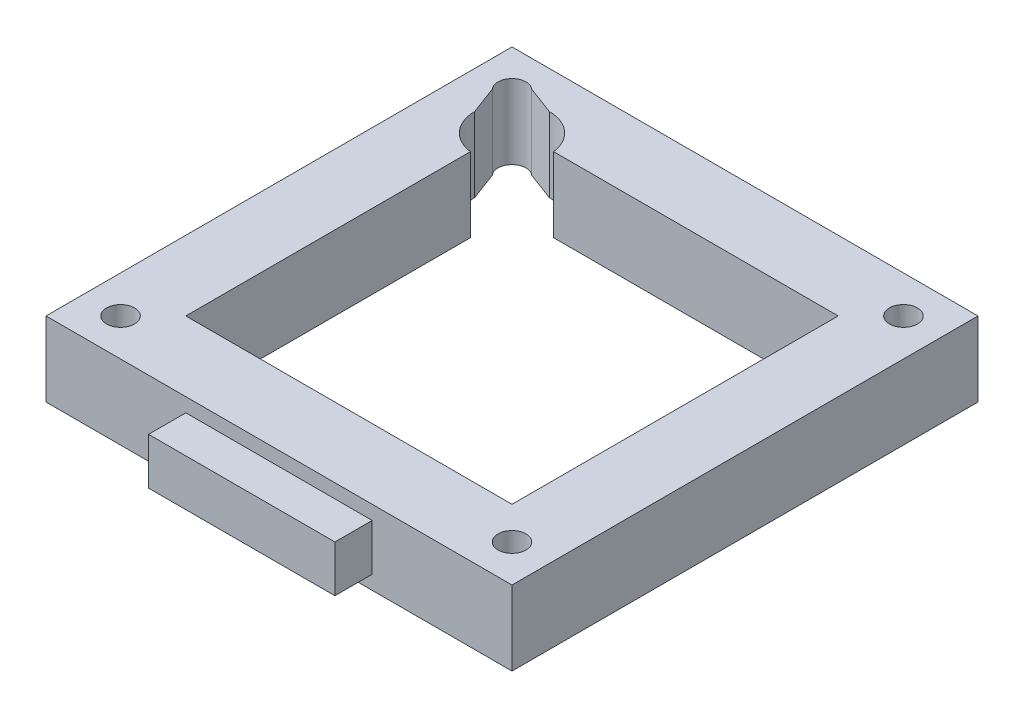
SolidWorks part; units mm, degrees
ref_plane "Front Plane" through (0, 0, 0) normal (0, 0, 1) x (1, 0, 0)
ref_plane "Top Plane" through (0, 0, 0) normal (0, 1, 0) x (1, 0, 0)
ref_plane "Right Plane" through (0, 0, 0) normal (1, 0, 0) x (0, 0, -1)
sketch "Sketch1" plane through (0, 0, 0) normal (0, 1, 0) x (1, 0, 0)
  line L0 (17.5, 17.5) -> (-13.0314, 17.5)
  line L1 (-25, -25) -> (25, -25)
  line L2 (-25, -25) -> (-25, 25)
  line L3 (-25, 25) -> (25, 25)
  line L4 (25, -25) -> (25, 25)
  line L5 (0, 25) -> (0, -25) construction
  line L6 (-25, 0) -> (25, 0) construction
  line L11 (0, 20) -> (0, -20) construction
  line L12 (-20, 0) -> (20, 0) construction
  line L13 (-17.5, -17.5) -> (17.5, -17.5)
  line L16 (17.5, -17.5) -> (17.5, 17.5)
  line L17 (0, 17.5) -> (0, -17.5) construction
  line L18 (-17.5, 0) -> (17.5, 0) construction
  line L19 (-17.5, -17.5) -> (-17.5, 13.0314)
  line L20 (-22.1301, 20.0137) -> (-21, 17)
  line L21 (-20.0137, 22.1301) -> (-17, 21)
  arc A0 (-20.0137, 22.1301) -> (-22.1301, 20.0137) centre (-21, 21) ccw
  circle A1 centre (21, 21) radius 1.5
  circle A2 centre (21, -21) radius 1.5
  circle A3 centre (-21, -21) radius 1.5
  arc A4 (-21, 17) -> (-17, 21) centre (-17, 17) ccw
  point P0 (0, 0)
  point P4 (0, 0)
  point P13 (0, 0)
  dimension "D1" = 50
  dimension "D2" = 50
  dimension "D4" = 35
extrude "Support" add sketch "Sketch1" along normal blind 8 contours L1 L4 L3 L2 A4 L0 L16 L13 L19 L20 A0 L21 A1 A2 A3
sketch "Sketch2" plane through (0, 0, 0) normal (0, 0, 1) x (1, 0, 0)
  line L4 (-10, 1.5) -> (10, 1.5)
  line L5 (-10, 1.5) -> (-10, 6.5)
  line L6 (-10, 6.5) -> (10, 6.5)
  line L7 (10, 1.5) -> (10, 6.5)
  line L8 (0, 6.5) -> (0, 1.5) construction
  line L9 (-10, 4) -> (10, 4) construction
  point P6 (0, 4)
  dimension "D1" = 20
  dimension "D2" = 5
extrude "South Dowel" add sketch "Sketch2" along normal blind 4 from surface at 25 starting at face at (0, 4, 25)
sketch "Sketch3" plane through (0, 0, 0) normal (1, 0, 0) x (0, 0, -1)
  line L4 (-10, 1.5) -> (10, 1.5)
  line L5 (-10, 1.5) -> (-10, 6.5)
  line L6 (-10, 6.5) -> (10, 6.5)
  line L7 (10, 1.5) -> (10, 6.5)
  line L8 (0, 6.5) -> (0, 1.5) construction
  line L9 (-10, 4) -> (10, 4) construction
  point P6 (0, 4)
  dimension "D1" = 20
  dimension "D2" = 5
extrude "West Cut" cut sketch "Sketch3" along normal blind 4 from surface at -25 starting at face at (-25, 4, 0)
